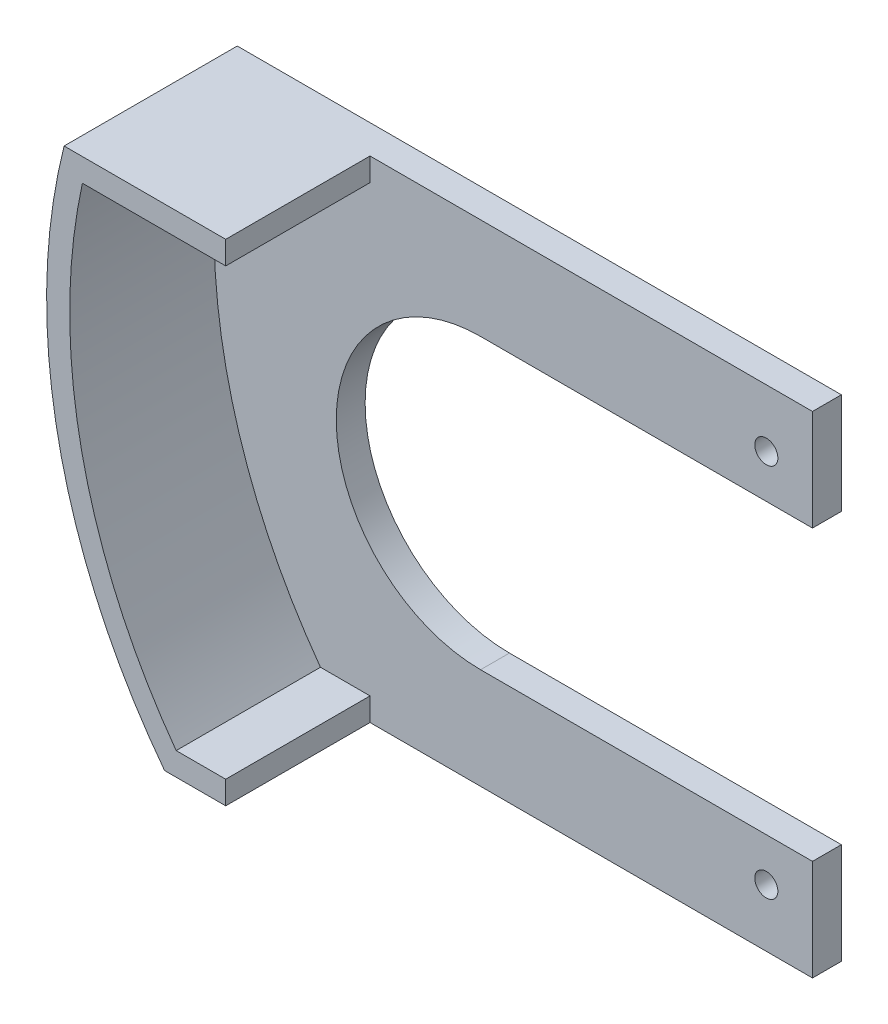
SolidWorks part; units mm, degrees
ref_plane "Front Plane" through (0, 0, 0) normal (0, 0, 1) x (1, 0, 0)
ref_plane "Top Plane" through (0, 0, 0) normal (0, 1, 0) x (1, 0, 0)
ref_plane "Right Plane" through (0, 0, 0) normal (1, 0, 0) x (0, 0, -1)
sketch "Sketch1" plane through (0, 0, 0) normal (0, 0, 1) x (1, 0, 0)
  line L0 (31.0104, -42.5) -> (41.6012, -42.5)
  line L1 (-95.5176, -42.5) -> (158.8436, -42.5) construction
  line L2 (41.6012, -42.5) -> (41.6012, -38.5)
  line L3 (33.0177, -38.5) -> (41.6012, -38.5)
  line L4 (13.6012, 42.5) -> (41.6012, 42.5)
  line L5 (156.7694, 42.5) -> (-99.6042, 42.5) construction
  line L6 (41.6012, 42.5) -> (41.6012, 38.5)
  line L7 (41.6012, 38.5) -> (16.7705, 38.5)
  line L8 (110.5733, -77.9216) -> (110.5733, -81.9216)
  line L9 (156.7694, 42.5) -> (-99.6042, 42.5) construction
  line L10 (-95.5176, -42.5) -> (158.8436, -42.5) construction
  circle A0 centre (110.5733, 18.0784) radius 100
  circle A2 centre (110.5733, 18.0784) radius 96
  circle A3 centre (60.7519, 0) radius 40 construction
  circle A5 centre (60.7519, 0) radius 43
  circle A6 centre (20.2519, 32.5) radius 2
  circle A7 centre (20.2519, 32.5) radius 2 construction
  dimension "D2" = 3
  dimension "D3" = 192
  dimension "D4" = 28
  dimension "D1" = 4
extrude "Boss-Extrude1" add sketch "Sketch1" along normal blind 30 contours L4 A2 L7 L6 | A2 L4 A0 L0 | L3 A2 L0 L2
sketch "Sketch2" plane through (0, 0, 0) normal (0, 0, 1) x (1, 0, 0)
  line L0 (41.6012, 42.5) -> (118.2519, 42.5)
  line L1 (156.7694, 42.5) -> (-99.6042, 42.5) construction
  line L2 (118.2519, 42.5) -> (118.2519, 25)
  line L3 (118.2519, 25) -> (60.7519, 25)
  line L4 (41.6012, -42.5) -> (118.2519, -42.5)
  line L5 (-95.5176, -42.5) -> (158.8436, -42.5) construction
  line L6 (118.2519, -42.5) -> (118.2519, -25)
  line L7 (118.2519, -25) -> (60.7519, -25)
  line L8 (118.2519, 32.5) -> (112.2519, 32.5)
  line L9 (112.2519, -32.5) -> (118.2519, -32.5)
  circle A0 centre (110.5733, 18.0784) radius 100
  circle A1 centre (60.7519, 0) radius 25
  circle A2 centre (60.7519, 0) radius 40 construction
  arc A4 (13.6012, 42.5) -> (31.0104, -42.5) centre (110.5733, 18.0784) ccw construction
  circle A8 centre (110.2519, 32.5) radius 2
  circle A9 centre (20.2519, 32.5) radius 2
  circle A10 centre (20.2519, -32.5) radius 2
  circle A11 centre (110.2519, -32.5) radius 2
  circle A12 centre (20.2519, 32.5) radius 2 construction
  dimension "D1" = 15
  dimension "D2" = 6
extrude "Boss-Extrude2" add sketch "Sketch2" along normal blind 5
